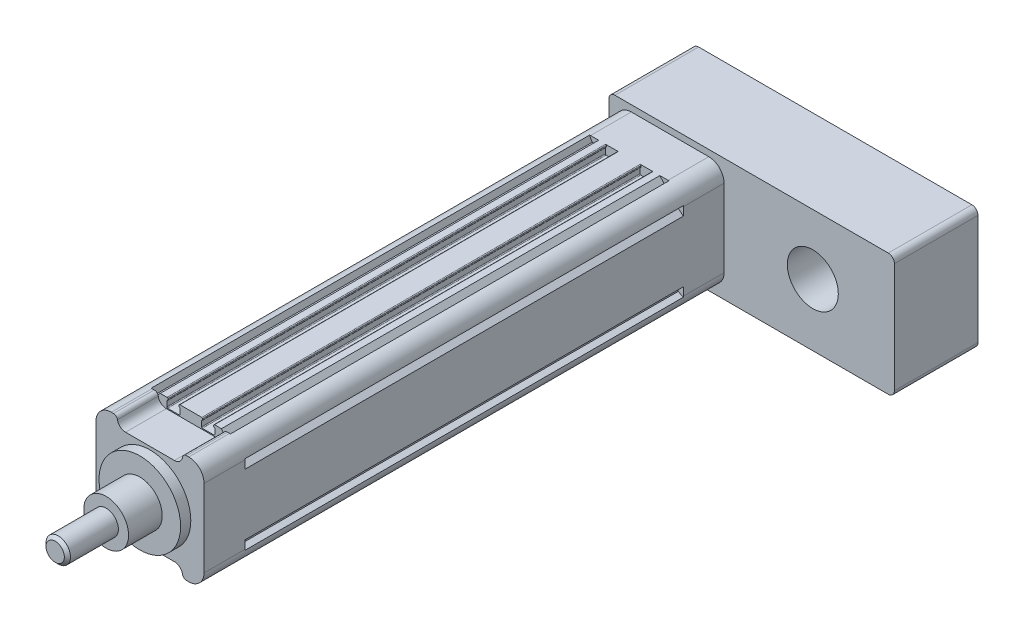
SolidWorks part; units mm, degrees
ref_plane "Front" through (0, 0, 0) normal (0, 0, 1) x (1, 0, 0)
ref_plane "Top" through (0, 0, 0) normal (0, 1, 0) x (1, 0, 0)
ref_plane "Right" through (0, 0, 0) normal (1, 0, 0) x (0, 0, -1)
sketch "草图1" plane through (0, 0, 0) normal (0, 0, 1) x (1, 0, 0)
  line L0 (19.7737, 3) -> (23.3, 3)
  line L1 (23.3, 3) -> (23.3, -3)
  line L2 (23.3, -3) -> (19.7737, -3)
  line L3 (-19.7737, -3) -> (-23.3, -3)
  line L4 (-23.3, -3) -> (-23.3, 3)
  line L5 (-23.3, 3) -> (-19.7737, 3)
  line L6 (-18.2, 24) -> (-19.4434, 26.4869)
  line L7 (-26.4869, 19.4434) -> (-24, 18.2)
  line L8 (-24, 18.2) -> (-24, 17.1)
  line L9 (-24, 17.1) -> (-26.5, 15)
  line L10 (-26.5, 15) -> (-26.5, -15)
  line L11 (-26.5, -15) -> (-24, -17.1)
  line L12 (-24, -17.1) -> (-24, -18.2)
  line L13 (-24, -18.2) -> (-26.4869, -19.4434)
  line L14 (-19.4434, -26.4869) -> (-18.2, -24)
  line L15 (-18.2, -24) -> (-17.1, -24)
  line L16 (-17.1, -24) -> (-15, -26.5)
  line L17 (-15, -26.5) -> (-11.65, -26.5)
  line L18 (-11.25, -26.1) -> (-11.25, -25.6)
  line L19 (-11.65, -25.2) -> (-11.75, -25.2)
  line L20 (-11.75, -25.2) -> (-11.75, -22.4)
  line L21 (-11.35, -22) -> (-5.65, -22)
  line L22 (-5.25, -22.4) -> (-5.25, -25.2)
  line L23 (-5.25, -25.2) -> (-5.35, -25.2)
  line L24 (-5.75, -25.6) -> (-5.75, -26.1)
  line L25 (-5.35, -26.5) -> (5.35, -26.5)
  line L26 (5.75, -26.1) -> (5.75, -25.6)
  line L27 (5.35, -25.2) -> (5.25, -25.2)
  line L28 (5.25, -25.2) -> (5.25, -22.4)
  line L29 (5.65, -22) -> (11.35, -22)
  line L30 (11.75, -22.4) -> (11.75, -25.2)
  line L31 (11.75, -25.2) -> (11.65, -25.2)
  line L32 (11.25, -25.6) -> (11.25, -26.1)
  line L33 (11.65, -26.5) -> (15, -26.5)
  line L34 (15, -26.5) -> (17.1, -24)
  line L35 (17.1, -24) -> (18.2, -24)
  line L36 (18.2, -24) -> (19.4434, -26.4869)
  line L37 (26.4869, -19.4434) -> (24, -18.2)
  line L38 (24, -18.2) -> (24, -17.1)
  line L39 (24, -17.1) -> (26.5, -15)
  line L40 (26.5, -15) -> (26.5, 15)
  line L41 (26.5, 15) -> (24, 17.1)
  line L42 (24, 17.1) -> (24, 18.2)
  line L43 (24, 18.2) -> (26.4869, 19.4434)
  line L44 (19.4434, 26.4869) -> (18.2, 24)
  line L45 (18.2, 24) -> (17.1, 24)
  line L46 (17.1, 24) -> (15, 26.5)
  line L47 (15, 26.5) -> (11.65, 26.5)
  line L48 (11.25, 26.1) -> (11.25, 25.6)
  line L49 (11.65, 25.2) -> (11.75, 25.2)
  line L50 (11.75, 25.2) -> (11.75, 22.4)
  line L51 (11.35, 22) -> (5.65, 22)
  line L52 (5.25, 22.4) -> (5.25, 25.2)
  line L53 (5.25, 25.2) -> (5.35, 25.2)
  line L54 (5.75, 25.6) -> (5.75, 26.1)
  line L55 (5.35, 26.5) -> (-5.35, 26.5)
  line L56 (-5.75, 26.1) -> (-5.75, 25.6)
  line L57 (-5.35, 25.2) -> (-5.25, 25.2)
  line L58 (-5.25, 25.2) -> (-5.25, 22.4)
  line L59 (-5.65, 22) -> (-11.35, 22)
  line L60 (-11.75, 22.4) -> (-11.75, 25.2)
  line L61 (-11.75, 25.2) -> (-11.65, 25.2)
  line L62 (-11.25, 25.6) -> (-11.25, 26.1)
  line L63 (-11.65, 26.5) -> (-15, 26.5)
  line L64 (-15, 26.5) -> (-17.1, 24)
  line L65 (-17.1, 24) -> (-18.2, 24)
  arc A0 (19.7737, 3) -> (-19.7737, 3) centre (0, 0) ccw
  arc A1 (-19.7737, -3) -> (19.7737, -3) centre (0, 0) ccw
  circle A2 centre (19, 19) radius 2.1
  circle A3 centre (19, -19) radius 2.1
  circle A4 centre (-19, -19) radius 2.1
  circle A5 centre (-19, 19) radius 2.1
  arc A6 (-19.4434, 26.4869) -> (-26.4869, 19.4434) centre (-19, 19) ccw
  arc A7 (-26.4869, -19.4434) -> (-19.4434, -26.4869) centre (-19, -19) ccw
  arc A8 (-11.65, -26.5) -> (-11.25, -26.1) centre (-11.65, -26.1) ccw
  arc A9 (-11.25, -25.6) -> (-11.65, -25.2) centre (-11.65, -25.6) ccw
  arc A10 (-11.35, -22) -> (-11.75, -22.4) centre (-11.35, -22.4) ccw
  arc A11 (-5.25, -22.4) -> (-5.65, -22) centre (-5.65, -22.4) ccw
  arc A12 (-5.35, -25.2) -> (-5.75, -25.6) centre (-5.35, -25.6) ccw
  arc A13 (-5.75, -26.1) -> (-5.35, -26.5) centre (-5.35, -26.1) ccw
  arc A14 (5.35, -26.5) -> (5.75, -26.1) centre (5.35, -26.1) ccw
  arc A15 (5.75, -25.6) -> (5.35, -25.2) centre (5.35, -25.6) ccw
  arc A16 (5.65, -22) -> (5.25, -22.4) centre (5.65, -22.4) ccw
  arc A17 (11.75, -22.4) -> (11.35, -22) centre (11.35, -22.4) ccw
  arc A18 (11.65, -25.2) -> (11.25, -25.6) centre (11.65, -25.6) ccw
  arc A19 (11.25, -26.1) -> (11.65, -26.5) centre (11.65, -26.1) ccw
  arc A20 (19.4434, -26.4869) -> (26.4869, -19.4434) centre (19, -19) ccw
  arc A21 (26.4869, 19.4434) -> (19.4434, 26.4869) centre (19, 19) ccw
  arc A22 (11.65, 26.5) -> (11.25, 26.1) centre (11.65, 26.1) ccw
  arc A23 (11.25, 25.6) -> (11.65, 25.2) centre (11.65, 25.6) ccw
  arc A24 (11.35, 22) -> (11.75, 22.4) centre (11.35, 22.4) ccw
  arc A25 (5.25, 22.4) -> (5.65, 22) centre (5.65, 22.4) ccw
  arc A26 (5.35, 25.2) -> (5.75, 25.6) centre (5.35, 25.6) ccw
  arc A27 (5.75, 26.1) -> (5.35, 26.5) centre (5.35, 26.1) ccw
  arc A28 (-5.35, 26.5) -> (-5.75, 26.1) centre (-5.35, 26.1) ccw
  arc A29 (-5.75, 25.6) -> (-5.35, 25.2) centre (-5.35, 25.6) ccw
  arc A30 (-5.65, 22) -> (-5.25, 22.4) centre (-5.65, 22.4) ccw
  arc A31 (-11.75, 22.4) -> (-11.35, 22) centre (-11.35, 22.4) ccw
  arc A32 (-11.65, 25.2) -> (-11.25, 25.6) centre (-11.65, 25.6) ccw
  arc A33 (-11.25, 26.1) -> (-11.65, 26.5) centre (-11.65, 26.1) ccw
extrude "凸台-拉伸1" add sketch "草图1" along normal blind 215
sketch "草图6" plane through (0, 0, 215) normal (0, 0, 1) x (1, 0, 0)
  line L0 (0, 0) -> (19, 0) construction
  line L2 (-26.5, -19) -> (-26.5, 19)
  line L3 (-19, 26.5) -> (-17.9161, 26.5)
  line L4 (26.5, -19) -> (26.5, 19)
  line L5 (-26.5, -26.5) -> (26.5, 26.5) construction
  line L6 (-26.5, 26.5) -> (26.5, -26.5) construction
  line L7 (-12, 21.5) -> (12, 21.5)
  line L9 (19, 26.5) -> (17.9161, 26.5)
  line L10 (19, -26.5) -> (17.9161, -26.5)
  line L11 (-12, -21.5) -> (12, -21.5)
  line L12 (-19, -26.5) -> (-17.9161, -26.5)
  arc A0 (12, 21.5) -> (15.9441, 24.8333) centre (12, 25.5) ccw
  arc A1 (-15.9441, 24.8333) -> (-12, 21.5) centre (-12, 25.5) ccw
  arc A2 (-15.9441, 24.8333) -> (-17.9161, 26.5) centre (-17.9161, 24.5) ccw
  arc A3 (15.9441, 24.8333) -> (17.9161, 26.5) centre (17.9161, 24.5) cw
  arc A4 (-26.5, -19) -> (-19, -26.5) centre (-19, -19) ccw
  arc A5 (19, -26.5) -> (26.5, -19) centre (19, -19) ccw
  arc A6 (26.5, 19) -> (19, 26.5) centre (19, 19) ccw
  arc A7 (-26.5, 19) -> (-19, 26.5) centre (-19, 19) cw
  arc A8 (15.9441, -24.8333) -> (17.9161, -26.5) centre (17.9161, -24.5) ccw
  arc A9 (12, -21.5) -> (15.9441, -24.8333) centre (12, -25.5) cw
  arc A10 (-15.9441, -24.8333) -> (-12, -21.5) centre (-12, -25.5) cw
  arc A11 (-15.9441, -24.8333) -> (-17.9161, -26.5) centre (-17.9161, -24.5) cw
  point P0 (0, 0)
  point P9 (0, 21.5)
  point P13 (20, 20.8461)
  point P16 (-12, 20.8461)
  dimension "D5" = 4
  dimension "D6" = 2
  dimension "D7" = 2
  dimension "D9" = 7.5
  dimension "D1" = 53
  dimension "D2" = 53
  dimension "D3" = 26.5
  dimension "D4" = 24
  dimension "D8" = 5
extrude "凸台-拉伸2" add sketch "草图6" along normal blind 20
sketch "草图7" plane through (0, 0, 235) normal (0, 0, 1) x (1, 0, 0)
  circle A0 centre (0, 0) radius 20
  dimension "D1" = 40
extrude "凸台-拉伸3" add sketch "草图7" along normal blind 5
sketch "草图9" plane through (0, 0, 240) normal (0, 0, 1) x (1, 0, 0)
  circle A0 centre (0, 0) radius 11
  dimension "D1" = 22
extrude "凸台-拉伸4" add sketch "草图9" along normal blind 16.5
sketch "草图10" plane through (0, 0, 256.5) normal (0, 0, 1) x (1, 0, 0)
  circle A0 centre (0, 0) radius 6
  dimension "D1" = 12
extrude "凸台-拉伸5" add sketch "草图10" along normal blind 25
sketch "草图11" plane through (0, 0, 0) normal (0, 0, -1) x (-1, 0, 0)
  line L1 (-19, -26.5) -> (19, -26.5)
  line L2 (-26.5, -19) -> (-26.5, 19)
  line L3 (-19, 26.5) -> (19, 26.5)
  line L4 (26.5, -19) -> (26.5, 19)
  line L5 (-26.5, -26.5) -> (26.5, 26.5) construction
  line L6 (-26.5, 26.5) -> (26.5, -26.5) construction
  arc A0 (-26.5, -19) -> (-19, -26.5) centre (-19, -19) ccw
  arc A1 (19, -26.5) -> (26.5, -19) centre (19, -19) ccw
  arc A2 (26.5, 19) -> (19, 26.5) centre (19, 19) ccw
  arc A3 (-26.5, 19) -> (-19, 26.5) centre (-19, 19) cw
  point P0 (0, 0)
  dimension "D3" = 7.5
  dimension "D1" = 53
  dimension "D2" = 53
extrude "凸台-拉伸6" add sketch "草图11" along normal blind 20
sketch "草图12" plane through (0, 0, -20) normal (0, 0, -1) x (-1, 0, 0)
  line L1 (-107, -30.4042) -> (27, -30.4042)
  line L2 (-110, -27.4042) -> (-110, 26.5958)
  line L3 (-107, 29.5958) -> (27, 29.5958)
  line L4 (30, -27.4042) -> (30, 26.5958)
  line L5 (-110, -30.4042) -> (30, 29.5958) construction
  line L6 (-110, 29.5958) -> (30, -30.4042) construction
  arc A0 (27, 29.5958) -> (30, 26.5958) centre (27, 26.5958) cw
  arc A1 (30, -27.4042) -> (27, -30.4042) centre (27, -27.4042) cw
  arc A2 (-110, -27.4042) -> (-107, -30.4042) centre (-107, -27.4042) ccw
  arc A3 (-110, 26.5958) -> (-107, 29.5958) centre (-107, 26.5958) cw
  point P0 (-40, -0.4042)
  dimension "D4" = 3
  dimension "D1" = 60
  dimension "D2" = 140
  dimension "D3" = 30
extrude "凸台-拉伸7" add sketch "草图12" along normal blind 41
sketch "草图13" plane through (0, 0, -20) normal (0, 0, 1) x (1, 0, 0)
  circle A0 centre (70, 0) radius 12.5
  dimension "D2" = 25
  dimension "D1" = 70
extrude "切除-拉伸2" cut sketch "草图13" against normal blind 30
hole_wizard "M6 螺纹孔1" positions "草图14" profile "草图15" tap size "M6" standard "GB"
sketch "草图14" plane through (0, 0, -61) normal (0, 0, -1) x (-1, 0, 0)
  line L0 (30, -27.4042) -> (30, 26.5958) construction
  point P0 (19, -19)
  dimension "D1" = 11
  dimension "D2" = 19
sketch "草图15" plane through (-19, -19, -61) normal (1, 0, 0) x (0, 1, 0)
  line L0 (0, 0) -> (0, 16.5022)
  line L1 (0, 16.5022) -> (2.5, 15)
  line L2 (2.5, 15) -> (2.5, 0)
  line L5 (2.5, 0) -> (0, 0)
  line L10 (0, 16.5022) -> (-2.5, 15) construction
  line L11 (0, -6.35) -> (0, 107.95) construction
  dimension "螺纹孔钻头直径" = 5
  dimension "螺纹孔钻头深度" = 15
  dimension "导头角度" = 118
cosmetic thread "孔螺蚊线4" parameters "D1"=12, "D2"=6
pattern_linear "阵列(线性)1" count 2 spacing 38 along (0, 1, 0) count 2 spacing 38 along (1, 0, 0) of "M6 螺纹孔1"
hole_wizard "M6 螺纹孔2" positions "草图16" profile "草图17" tap size "M6" standard "GB"
sketch "草图16" plane through (0, 0, -61) normal (0, 0, -1) x (-1, 0, 0)
  circle A1 centre (-19, 19) radius 2.5 construction
  circle A2 centre (-19, -19) radius 2.5 construction
  point P0 (-84, -19)
  point P2 (-84, 19)
  dimension "D3" = 65
  dimension "D1" = 19
  dimension "D2" = 19
  dimension "D4" = 65
sketch "草图17" plane through (84, -19, -61) normal (1, 0, 0) x (0, 1, 0)
  line L0 (0, 0) -> (0, 16.5022)
  line L1 (0, 16.5022) -> (2.5, 15)
  line L2 (2.5, 15) -> (2.5, 0)
  line L5 (2.5, 0) -> (0, 0)
  line L10 (0, 16.5022) -> (-2.5, 15) construction
  line L11 (0, -6.35) -> (0, 107.95) construction
  dimension "螺纹孔钻头直径" = 5
  dimension "螺纹孔钻头深度" = 15
  dimension "导头角度" = 118
cosmetic thread "孔螺蚊线5" parameters "D1"=12, "D2"=6
cosmetic thread "孔螺蚊线6" parameters "D1"=12, "D2"=6
hole_wizard "M6 螺纹孔3" positions "草图19" profile "草图20" tap size "M6" standard "GB"
sketch "草图19" plane through (-26.5, 0, 0) normal (-1, 0, 0) x (0, 0, 1)
  line L0 (235, 19) -> (235, -19) construction
  point P0 (225, 11)
  point P2 (225, -11)
  dimension "D1" = 10
  dimension "D2" = 10
  dimension "D3" = 22
  dimension "D4" = 11
sketch "草图20" plane through (-26.5, 11, 225) normal (0, 1, 0) x (0, 0, 1)
  line L0 (0, 0) -> (0, 16.5022)
  line L1 (0, 16.5022) -> (2.5, 15)
  line L2 (2.5, 15) -> (2.5, 0)
  line L5 (2.5, 0) -> (0, 0)
  line L10 (0, 16.5022) -> (-2.5, 15) construction
  line L11 (0, -6.35) -> (0, 107.95) construction
  dimension "螺纹孔钻头直径" = 5
  dimension "螺纹孔钻头深度" = 15
  dimension "导头角度" = 118
cosmetic thread "孔螺蚊线7" parameters "D1"=12, "D2"=6
cosmetic thread "孔螺蚊线8" parameters "D1"=12, "D2"=6
hole_wizard "M6 螺纹孔4" positions "草图21" profile "草图22" tap size "M6" standard "GB"
sketch "草图21" plane through (-26.5, 0, 0) normal (-1, 0, 0) x (0, 0, 1)
  line L0 (-20, -27.4042) -> (-20, 26.5958) construction
  line L1 (-20, -19) -> (-20, 19) construction
  point P0 (-10, 11)
  point P2 (-10, -11)
  dimension "D1" = 10
  dimension "D2" = 10
  dimension "D3" = 11
  dimension "D4" = 11
sketch "草图22" plane through (-26.5, 11, -10) normal (0, 1, 0) x (0, 0, 1)
  line L0 (0, 0) -> (0, 16.5022)
  line L1 (0, 16.5022) -> (2.5, 15)
  line L2 (2.5, 15) -> (2.5, 0)
  line L5 (2.5, 0) -> (0, 0)
  line L10 (0, 16.5022) -> (-2.5, 15) construction
  line L11 (0, -6.35) -> (0, 107.95) construction
  dimension "螺纹孔钻头直径" = 5
  dimension "螺纹孔钻头深度" = 15
  dimension "导头角度" = 118
cosmetic thread "孔螺蚊线9" parameters "D1"=12, "D2"=6
cosmetic thread "孔螺蚊线10" parameters "D1"=12, "D2"=6
chamfer "倒角1" distance 1.5 angle 45 1 edges at (6, 0, 281.5)
sketch "草图23" plane through (0, 0, 256.5) normal (0, 0, 1) x (1, 0, 0)
  line L1 (10.9697, 0) -> (5.4848, 9.5)
  line L2 (5.4848, 9.5) -> (-5.4848, 9.5)
  line L3 (-5.4848, 9.5) -> (-10.9697, 0)
  line L4 (-10.9697, 0) -> (-5.4848, -9.5)
  line L5 (-5.4848, -9.5) -> (5.4848, -9.5)
  line L6 (5.4848, -9.5) -> (10.9697, 0)
  circle A0 centre (0, 0) radius 9.5 construction
  dimension "D1" = 19
